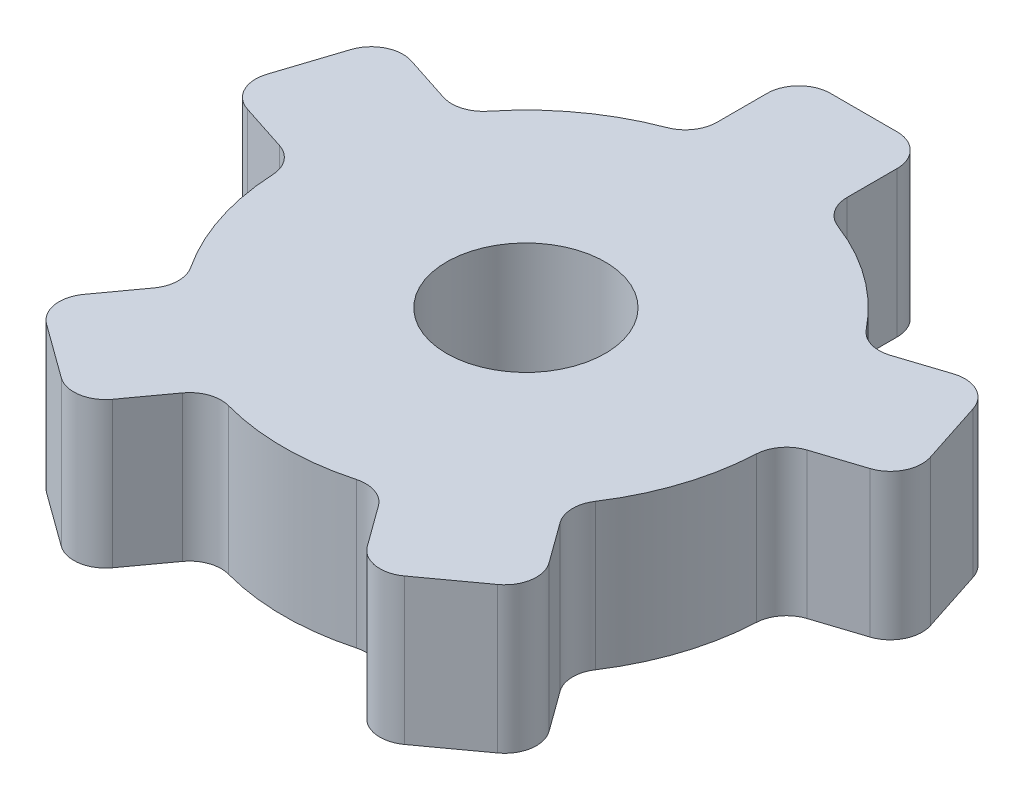
SolidWorks part; units mm, degrees
ref_plane "Front Plane" through (0, 0, 0) normal (0, 0, 1) x (1, 0, 0)
ref_plane "Top Plane" through (0, 0, 0) normal (0, 1, 0) x (1, 0, 0)
ref_plane "Right Plane" through (0, 0, 0) normal (1, 0, 0) x (0, 0, -1)
sketch "Sketch2" plane through (0, 0, 0) normal (0, 1, 0) x (1, 0, 0)
  line L0 (-5.207, 27.051) -> (5.207, 27.051)
  line L1 (5.207, 27.051) -> (5.207, 18.669)
  line L2 (-5.207, 27.051) -> (-5.207, 18.669)
  line L3 (24.118, 13.3114) -> (16.1462, 10.7212)
  line L4 (24.118, 13.3114) -> (27.3361, 3.4071)
  line L5 (27.3361, 3.4071) -> (19.3643, 0.8169)
  line L6 (20.1127, -18.8241) -> (15.1859, -12.0429)
  line L7 (20.1127, -18.8241) -> (11.6876, -24.9453)
  line L8 (11.6876, -24.9453) -> (6.7608, -18.1641)
  line L9 (-11.6876, -24.9453) -> (-6.7608, -18.1641)
  line L10 (-11.6876, -24.9453) -> (-20.1127, -18.8241)
  line L11 (-20.1127, -18.8241) -> (-15.1859, -12.0429)
  line L12 (-27.3361, 3.4071) -> (-19.3643, 0.8169)
  line L13 (-27.3361, 3.4071) -> (-24.118, 13.3114)
  line L14 (-24.118, 13.3114) -> (-16.1462, 10.7212)
  circle A0 centre (0, 0) radius 6.35
  arc A1 (-16.1462, 10.7212) -> (-5.207, 18.669) centre (0, 0) cw
  arc A2 (5.207, 18.669) -> (16.1462, 10.7212) centre (0, 0) cw
  arc A3 (19.3643, 0.8169) -> (15.1859, -12.0429) centre (0, 0) cw
  arc A4 (6.7608, -18.1641) -> (-6.7608, -18.1641) centre (0, 0) cw
  arc A5 (-19.3643, 0.8169) -> (-15.1859, -12.0429) centre (0, 0) ccw
  circle A6 centre (0, 0) radius 27.051 construction
  point P7 (0, 27.051)
  point P27 (0, 0)
  dimension "D4" = 54.102
  dimension "D5" = 12.7
  dimension "D1" = 10.414
  dimension "D2" = 8.382
  dimension "D3" = 5
extrude "Boss-Extrude3" add sketch "Sketch2" along normal blind 11.684
fillet "Fillet1" radius 2.54 20 edges at (-19.3643, 5.842, -0.8169) (-15.1859, 5.842, 12.0429) (-20.1127, 5.842, 18.8241) (-11.6876, 5.842, 24.9453) (-6.7608, 5.842, 18.1641) (11.6876, 5.842, 24.9453) (6.7608, 5.842, 18.1641) (15.1859, 5.842, 12.0429) (20.1127, 5.842, 18.8241) (19.3643, 5.842, -0.8169) (27.3361, 5.842, -3.4071) (24.118, 5.842, -13.3114) (16.1462, 5.842, -10.7212) (5.207, 5.842, -18.669) (5.207, 5.842, -27.051) (-5.207, 5.842, -18.669) (-5.207, 5.842, -27.051) (-16.1462, 5.842, -10.7212) (-24.118, 5.842, -13.3114) (-27.3361, 5.842, -3.4071)
